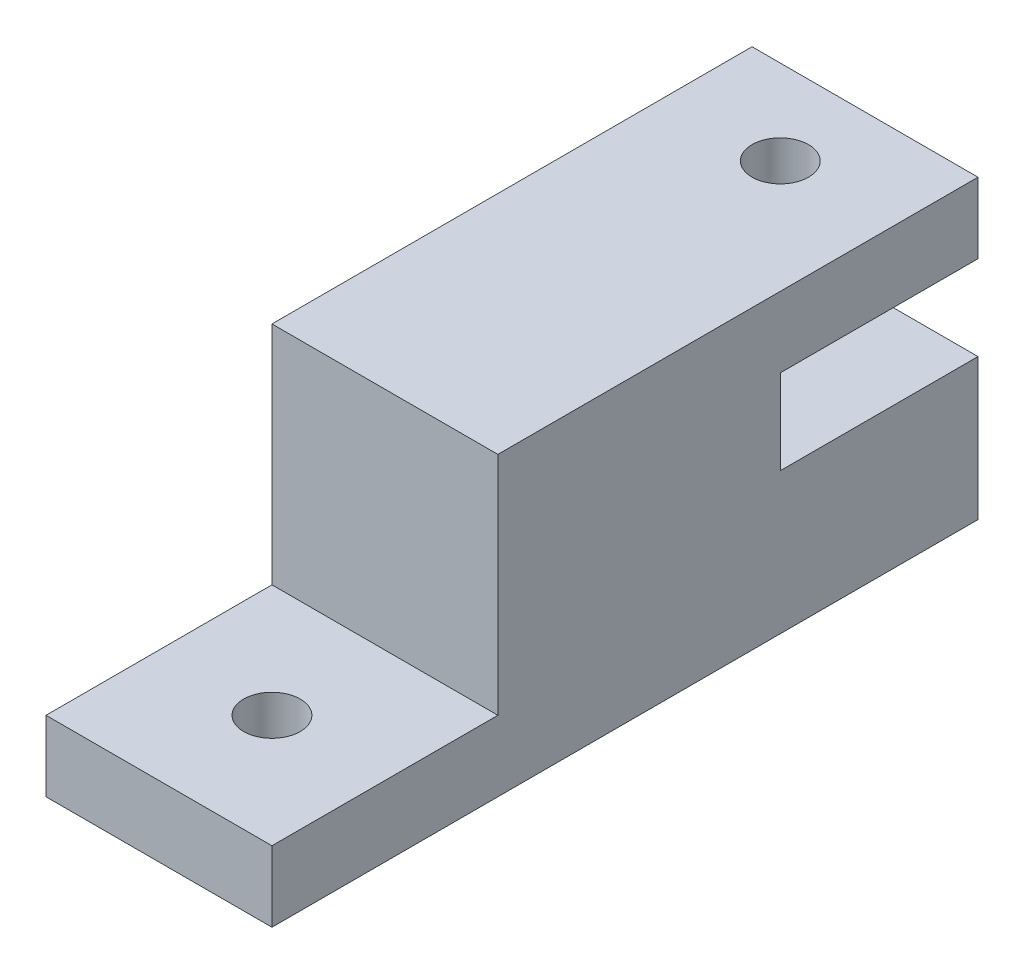
SolidWorks part; units mm, degrees
material "6061-T6 (SS)"
ref_plane "Front" through (0, 0, 0) normal (0, 0, 1) x (1, 0, 0)
ref_plane "Top" through (0, 0, 0) normal (0, 1, 0) x (1, 0, 0)
ref_plane "Right" through (0, 0, 0) normal (1, 0, 0) x (0, 0, -1)
sketch "Sketch1" plane through (0, 0, 0) normal (1, 0, 0) x (0, 0, -1)
  line L0 (0, 0) -> (-25.4, 0)
  line L1 (-25.4, 0) -> (-25.4, -7.9375)
  line L2 (-25.4, -7.9375) -> (53.975, -7.9375)
  line L3 (53.975, -7.9375) -> (53.975, 7.9375)
  line L4 (53.975, 25.4) -> (0, 25.4)
  line L5 (0, 25.4) -> (0, 0)
  line L6 (53.975, 17.4625) -> (31.75, 17.4625)
  line L7 (31.75, 17.4625) -> (31.75, 7.9375)
  line L8 (31.75, 7.9375) -> (53.975, 7.9375)
  line L9 (53.975, 17.4625) -> (53.975, 25.4)
  dimension "D1" = 25.4
  dimension "D2" = 25.4
  dimension "D3" = 7.9375
  dimension "D4" = 53.975
  dimension "D5" = 9.525
  dimension "D6" = 22.225
  dimension "D7" = 7.9375
extrude "Boss-Extrude1" add sketch "Sketch1" along normal mid plane 25.4
sketch "Sketch2" plane through (0, 25.4, 0) normal (0, 1, 0) x (1, 0, 0)
  line L0 (12.7, 53.975) -> (-12.7, 53.975) construction
  line L1 (12.7, -25.4) -> (-12.7, -25.4) construction
  circle A0 centre (0, 44.45) radius 3.175
  circle A1 centre (0, -12.7) radius 3.175
  dimension "D1" = 6.35
  dimension "D2" = 9.525
  dimension "D3" = 6.35
  dimension "D4" = 12.7
extrude "Cut-Extrude1" cut sketch "Sketch2" against normal through all
